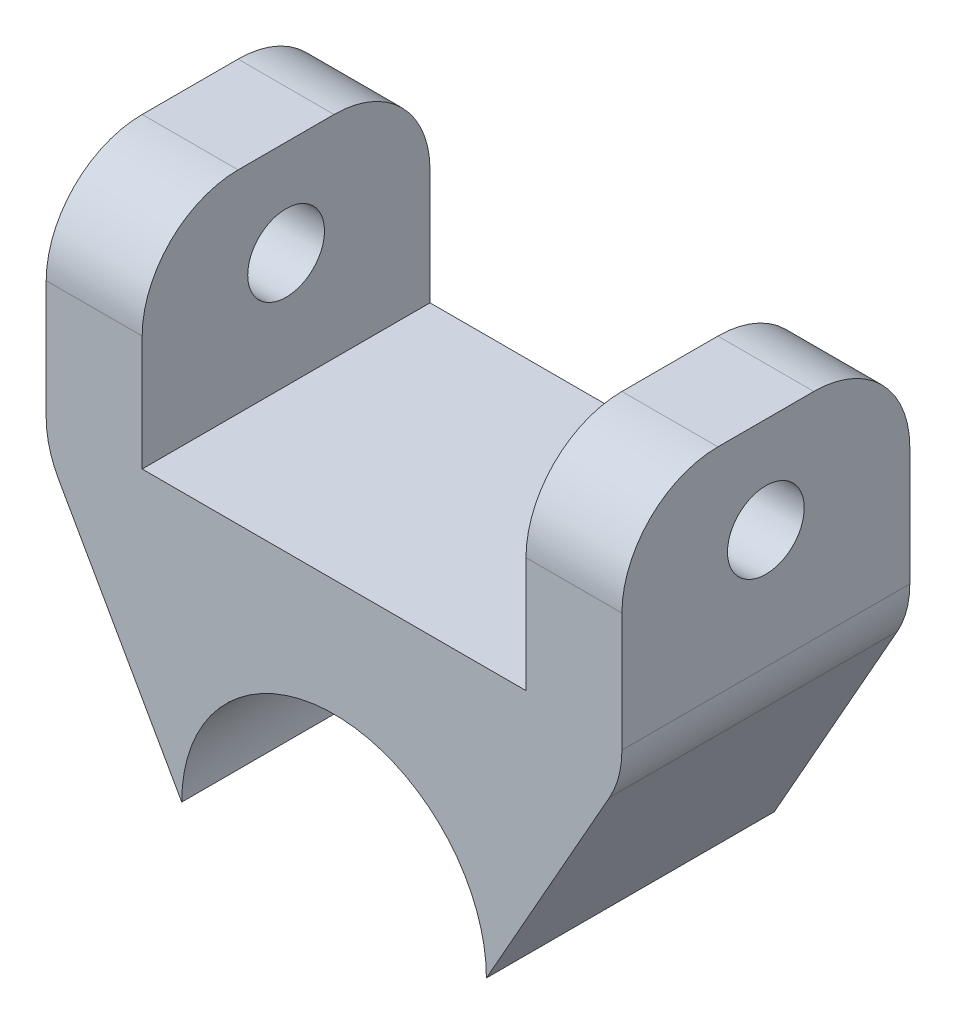
SolidWorks part; units mm, degrees
ref_plane "Front Plane" through (0, 0, 0) normal (0, 0, 1) x (1, 0, 0)
ref_plane "Top Plane" through (0, 0, 0) normal (0, 1, 0) x (1, 0, 0)
ref_plane "Right Plane" through (0, 0, 0) normal (1, 0, 0) x (0, 0, -1)
sketch "Sketch1" plane through (0, 0, 0) normal (0, 0, 1) x (1, 0, 0)
  line L2 (-15.875, 25) -> (-15.875, 7)
  line L4 (15.875, 25) -> (15.875, 7)
  line L5 (-15.875, 25) -> (15.875, -25) construction
  line L6 (-15.875, -25) -> (15.875, 25) construction
  line L7 (-30, 0) -> (-30, 25)
  line L9 (30, 0) -> (30, 25)
  line L10 (-30, 0) -> (30, 25) construction
  line L11 (-15.875, 7) -> (15.875, 7)
  line L14 (-30, 25) -> (-15.875, 25)
  line L15 (15.875, 25) -> (30, 25)
  line L16 (-30, 0) -> (-15.875, -25)
  line L17 (15.875, -25) -> (30, 0)
  arc A0 (-15.875, -25) -> (15.875, -25) centre (0, -25) cw
  point P0 (0, 0)
  point P13 (0, 12.5)
  dimension "D3" = 31.75
  dimension "D1" = 60
  dimension "D2" = 50
  dimension "D4" = 25
  dimension "D5" = 18
extrude "Boss-Extrude1" add sketch "Sketch1" along normal blind 30
fillet "Fillet1" radius 10 4 edges at (22.9375, 25, 0) (22.9375, 25, 30) (-22.9375, 25, 0) (-22.9375, 25, 30)
sketch "Sketch2" plane through (-30, 0, 0) normal (-1, 0, 0) x (0, 0, 1)
  line L0 (20, 25) -> (10, 25) construction
  circle A0 centre (15, 15) radius 4
  point P6 (15, 25)
  dimension "D1" = 8
extrude "Cut-Extrude1" cut sketch "Sketch2" against normal through all
sketch "Sketch4" plane through (0, 0, 30) normal (0, 0, 1) x (1, 0, 0)
  line L6 (-20, 3) -> (20, 3)
  line L8 (-20, 3) -> (-20, 25)
  line L9 (-20, 25) -> (20, 25)
  line L10 (20, 3) -> (20, 25)
  line L11 (-30, 25) -> (-15.875, 25) construction
  line L12 (-15.875, 15) -> (-30, 15) construction
  line L13 (-30, 25) -> (-30, 15) construction
  line L14 (30, 15) -> (30, 25) construction
  dimension "D1" = 12
  dimension "D2" = 10
  dimension "D3" = 10
extrude "Cut-Extrude2" cut sketch "Sketch4" against normal through all
fillet "Fillet2" radius 10 2 edges at (30, 0, 15) (-30, 0, 15)
